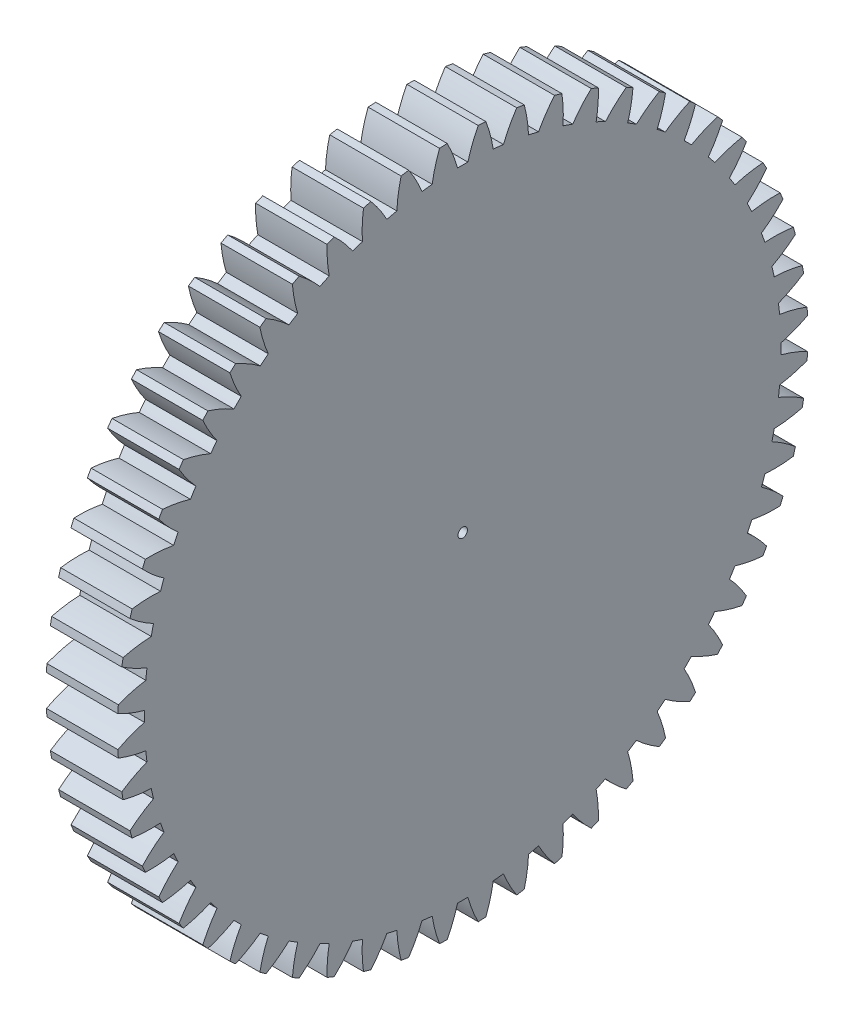
SolidWorks part; units mm, degrees
ref_plane "Plane1" through (0, 0, 0) normal (0, 0, 1) x (1, 0, 0)
ref_plane "Plane2" through (0, 0, 0) normal (0, 1, 0) x (1, 0, 0)
ref_plane "Plane3" through (0, 0, 0) normal (1, 0, 0) x (0, 0, -1)
other "Configuration Table"
sketch "HoldingSke" plane through (0, 0, 0) normal (0, 1, 0) x (1, 0, 0)
  line L0 (0, 0) -> (0.5592, -0.829)
  line L1 (-15, 0) -> (100, 0) construction
  line L2 (0, 0) -> (-2.1039, 2.3779)
  line L3 (0, 0) -> (-11.863, 4.5341)
  line L4 (0, 0) -> (4.8292, 7.1596)
  line L5 (0, 0) -> (-46.8476, -17.4728)
  line L6 (0, 0) -> (-4.9738, -3.3558)
  line L7 (-2.1039, 2.3779) -> (8.6586, 51.2059)
  line L8 (-76.2, 54.61) -> (-76.1, 54.61)
  line L9 (-71.009, 38.7566) -> (-53.1078, 45.2721)
  line L10 (-76.2, 71.12) -> (104.1128, 71.12)
  line L11 (0, 0) -> (-6, 0)
  line L12 (-76.2, 101.6) -> (-76.162, 101.6)
  line L13 (24.9733, 27.94) -> (52.9518, 28.4284)
  line L14 (24.9733, 27.94) -> (24.9743, 27.94)
  line L15 (24.9733, 27.94) -> (100.4006, 29.5858)
  line L16 (-63.627, -1) -> (-12.827, -1)
  circle A0 centre (0, 0) radius 0.4
  circle A1 centre (0, 0) radius 26.749
  circle A2 centre (0, 0) radius 37.5
  circle A3 centre (0, 0) radius 0.4
  dimension "MHD" = 53.498
  dimension "Hub_dia" = 75
  dimension "Bore" = 0.8
  dimension "MBD" = 0.8
  dimension "Num_teeth" = 56
  dimension "Pitch" = 1
  dimension "Overall_len" = 50
  dimension "Show_teeth" = 56
  dimension "Thickness" = 6
  dimension "OAL" = 50.0001
  dimension "T_dim" = 0.1
  dimension "Ap" = 20
  dimension "H" = 19.05
  dimension "Pitch_radius" = 180.3128
  dimension "Width" = 6
  dimension "Backlash" = 0.038
  dimension "Addendum_fac" = 1
  dimension "Dedendum_fac" = 1.25
  dimension "Clearance_fac" = 0.25
  dimension "Dedendum_add" = 0.001
  dimension "Module" = 1
sketch "BasProSke" plane through (0, 0, 0) normal (0, 1, 0) x (1, 0, 0)
  line L0 (-10, 0) -> (60, 0) construction
  line L1 (0, 0) -> (0, 29)
  line L2 (0, 0) -> (6, 0)
  line L3 (6, 0) -> (6, 29)
  line L4 (6, 29) -> (0, 29)
  dimension "Thickness" = 6
  dimension "Diameter" = 58
revolve "Base-Revolve" add sketch "BasProSke" angle 360 about L0
sketch "TooCutSke" plane through (0, 0, 0) normal (1, 0, 0) x (0, 0, -1)
  line L1 (0, 0) -> (0, 107) construction
  line L2 (0, 0) -> (-0.8518, 27.987) construction
  line L3 (0, 0) -> (-3.1389, 55.8935) construction
  line L4 (-0.8518, 27.987) -> (-1.5695, 27.9467) construction
  arc A0 (0.4329, 26.7455) -> (-0.4329, 26.7455) centre (0, 0) ccw
  arc A1 (1.3187, 28.9954) -> (-1.3187, 28.9954) centre (0, 0) ccw
  circle A2 centre (0, 0) radius 28 construction
  circle A3 centre (0, 0) radius 26.3114 construction
  arc A4 (-0.4329, 26.7455) -> (-1.3187, 28.9954) centre (-11.2363, 23.7915) ccw
  arc A5 (1.3187, 28.9954) -> (0.4329, 26.7455) centre (11.2363, 23.7915) ccw
  dimension "Root_dia" = 53.498
  dimension "Overcut_dia" = 58.0508
  dimension "Pitch_dia" = 56
  dimension "Base_dia" = 52.6228
  dimension "Flank_rad" = 11.2
  dimension "Half_ang" = 3.214
  dimension "Half_CT" = 0.7188
extrude "ToothCut" cut sketch "TooCutSke" along normal through all
fillet "Breaks" [suppressed] radius 0.02
fillet "RootFillets" [suppressed] radius 0.251
pattern_circular "TeethCuts" count 56 every 6.429 about axis through (-10, 0, 0) along (1, 0, 0) of "ToothCut", "RootFillets", "Breaks"
sketch "HubNeaOneSke" plane through (0, 0, 0) normal (-1, 0, 0) x (0, 0, 1)
  circle A0 centre (0, 0) radius 26.749
  dimension "Diameter" = 53.498
extrude "HubNearOne" [suppressed] add sketch "HubNeaOneSke" along normal blind 44.0001
sketch "HubNeaBotSke" plane through (0, 0, 0) normal (-1, 0, 0) x (0, 0, 1)
  circle A0 centre (0, 0) radius 26.749
  dimension "Diameter" = 53.498
extrude "HubNearBoth" [suppressed] add sketch "HubNeaBotSke" along normal blind 22
ref_plane "FarPln" through (6, 0, 0) normal (1, 0, 0) x (0, 0, -1)
sketch "HubFarSke" plane through (6, 0, 0) normal (1, 0, 0) x (0, 0, -1)
  circle A0 centre (0, 0) radius 26.749
  dimension "Diameter" = 53.498
extrude "HubFar" [suppressed] add sketch "HubFarSke" along normal blind 22
sketch "BorSke" plane through (0, 0, 0) normal (1, 0, 0) x (0, 0, -1)
  circle A0 centre (0, 0) radius 0.4
  dimension "Diameter" = 0.8
extrude "Bore" cut sketch "BorSke" along normal mid plane 100.0001
sketch "KeySke" plane through (0, 0, 0) normal (1, 0, 0) x (0, 0, -1)
  line L0 (-0.05, 0) -> (-0.05, 0.5)
  line L1 (-0.05, 0.5) -> (0.05, 0.5)
  line L2 (0.05, 0.5) -> (0.05, 0)
  line L3 (0, 0) -> (0, 34) construction
  line L4 (-0.05, 0) -> (0.05, 0)
  dimension "Offset" = 0.5
  dimension "Width" = 0.1
extrude "Keyway" [suppressed] cut sketch "KeySke" along normal mid plane 100.0001
pattern_circular "Keyway2" [suppressed] count 2 every 90 about axis through (-10, 0, 0) along (1, 0, 0)
equation "' \"Module@HoldingSke\" = 6.35"
equation "' \"Num_teeth@HoldingSke\" = 12"
equation "' \"Ap@HoldingSke\" =  20"
equation "' \"Ap@HoldingSke\" = 20"
equation "' \"Width@HoldingSke\" = 0.5 * 25.4"
equation "' \"Hub_dia@HoldingSke\"= 1 * 25.4"
equation "' \"Hub_dia@HoldingSke\" = 1 * 25.4"
equation "' \"Overall_len@HoldingSke\" = 1.0 * 25.4"
equation "' \"Bore@HoldingSke\" = 0.75 * 25.4"
equation "' \"T_dim@HoldingSke\" = 0.1 * 25.4"
equation "' \"Width@KeySke\" = 0.25 * 25.4"
equation "' \"Show_teeth@HoldingSke\" = 13"
equation "' \"Backlash@HoldingSke\" = 0.009 * 25.4"
equation "' \"Addendum_fac@HoldingSke\" = 1.0"
equation "' \"Dedendum_fac@HoldingSke\" = 1.25"
equation "' \"Dedendum_add@HoldingSke\" = 0.00005 * 25.4"
equation "' \"Clearance_fac@HoldingSke\" = 0.25"
equation "\"Pitch@HoldingSke\" = 1 / \"Module@HoldingSke\""
equation "\"Overcut_dia@TooCutSke\" = (\"Num_teeth@HoldingSke\" + 2 * \"Addendum_fac@HoldingSke\") / \"Pitch@HoldingSke\" + 0.002 * 25.4"
equation "\"Pitch_dia@TooCutSke\" = \"Num_teeth@HoldingSke\" / \"Pitch@HoldingSke\""
equation "\"Base_dia@TooCutSke\" = \"Num_teeth@HoldingSke\" / \"Pitch@HoldingSke\" * cos((\"Ap@HoldingSke\"  * 3.14159265 / 180))"
equation "\"Root_dia@TooCutSke\" = (\"Num_teeth@HoldingSke\" + 2) / \"Pitch@HoldingSke\" - 2 * (\"Addendum_fac@HoldingSke\" + \"Dedendum_fac@HoldingSke\") / \"Pitch@HoldingSke\" - \"Dedendum_add@HoldingSke\" * 2"
equation "\"Half_ang@TooCutSke\" = 180 / \"Num_teeth@HoldingSke\""
equation "\"Half_CT@TooCutSke\" = \"Num_teeth@HoldingSke\" / \"Pitch@HoldingSke\" * sin((3.14159265 / 2 / \"Num_teeth@HoldingSke\")) / 2 - 7 * \"Backlash@HoldingSke\" / 4"
equation "\"Flank_rad@TooCutSke\" = \"Num_teeth@HoldingSke\" / \"Pitch@HoldingSke\" / 5"
equation "\"Radius@RootFillets\" = \"Clearance_fac@HoldingSke\" / \"Pitch@HoldingSke\" + \"Dedendum_add@HoldingSke\""
equation "\"Break_rad@Breaks\" = 0.02 / \"Pitch@HoldingSke\""
equation "\"Thickness@HoldingSke\" = \"Width@HoldingSke\""
equation "\"OAL@HoldingSke\" = \"Thickness@HoldingSke\""
equation "\"MHD@HoldingSke\" = (\"Num_teeth@HoldingSke\" + 2) / \"Pitch@HoldingSke\" - 2 * (\"Addendum_fac@HoldingSke\" + \"Dedendum_fac@HoldingSke\")  / \"Pitch@HoldingSke\" - \"Dedendum_add@HoldingSke\" * 2"
equation "\"MBD@HoldingSke\" = (\"Num_teeth@HoldingSke\" + 2) / \"Pitch@HoldingSke\" - 2 * (\"Addendum_fac@HoldingSke\" + \"Dedendum_fac@HoldingSke\")  / \"Pitch@HoldingSke\" - \"Dedendum_add@HoldingSke\" * 2 - 0.002 * 25.4"
equation "\"MHD@HoldingSke\" = ((sgn( \"MHD@HoldingSke\" - \"Hub_dia@HoldingSke\" )-1)*( \"MHD@HoldingSke\" - \"Hub_dia@HoldingSke\" ))/-2+ \"Hub_dia@HoldingSke\""
equation "\"MBD@HoldingSke\" = ((sgn( \"MBD@HoldingSke\" - \"Bore@HoldingSke\" )-1)*( \"MBD@HoldingSke\" - \"Bore@HoldingSke\" ))/-2+ \"Bore@HoldingSke\""
equation "\"OAL@HoldingSke\" = ((sgn( \"OAL@HoldingSke\" - \"Overall_len@HoldingSke\" )+1)*( \"OAL@HoldingSke\" - \"Overall_len@HoldingSke\" ))/2 + \"Overall_len@HoldingSke\" + 0.000002 * 25.4"
equation "\"Num_teeth@TeethCuts\" = int( \"Show_teeth@HoldingSke\" ) + 1"
equation "\"Num_teeth@TeethCuts\" = ((sgn( \"Num_teeth@TeethCuts\" - \"Num_teeth@HoldingSke\" )-1)*( \"Num_teeth@TeethCuts\" - \"Num_teeth@HoldingSke\" ))/-2+ \"Num_teeth@HoldingSke\""
equation "\"Num_teeth@TeethCuts\" = ((sgn( \"Num_teeth@TeethCuts\" - 2.0)+1)*( \"Num_teeth@TeethCuts\" - 2.0))/2 +2.0"
equation "\"Angle@TeethCuts\" = 360.0 / \"Num_teeth@HoldingSke\""
equation "\"Diameter@BasProSke\" = (\"Num_teeth@HoldingSke\" + 2 * \"Addendum_fac@HoldingSke\") / \"Pitch@HoldingSke\""
equation "\"Thickness@BasProSke\"  = \"Thickness@HoldingSke\""
equation "' \"Fillet_rad@BasProSke\" =  \"Thickness@HoldingSke\" * 0.05"
equation "' \"Fillet_rad@BasProSke\" = \"Thickness@HoldingSke\" * 0.05"
equation "\"MHD@HoldingSke\" = ((sgn( \"MHD@HoldingSke\" - \"Root_dia@TooCutSke\" )-1)*( \"MHD@HoldingSke\" - \"Root_dia@TooCutSke\" ))/-2+ \"Root_dia@TooCutSke\""
equation "\"Diameter@HubNeaOneSke\" = \"MHD@HoldingSke\""
equation "\"Length@HubNearOne\" = \"OAL@HoldingSke\" - \"Thickness@BasProSke\""
equation "\"Diameter@HubNeaBotSke\" = \"MHD@HoldingSke\""
equation "\"Length@HubNearBoth\" = ( \"OAL@HoldingSke\" - \"Thickness@BasProSke\" ) / 2.0"
equation "\"Thickness@FarPln\" = \"Thickness@BasProSke\""
equation "\"Diameter@HubFarSke\" = \"MHD@HoldingSke\""
equation "\"Length@HubFar\" = ( \"OAL@HoldingSke\" - \"Thickness@BasProSke\" ) / 2.0"
equation "\"Diameter@BorSke\" = \"MBD@HoldingSke\""
equation "\"D1@Bore\" = \"OAL@HoldingSke\" * 2.0"
equation "\"D1@Keyway\" = \"OAL@HoldingSke\" * 2.0"
equation "\"Offset@KeySke\" = \"T_dim@HoldingSke\" + \"MBD@HoldingSke\" / 2.0"
